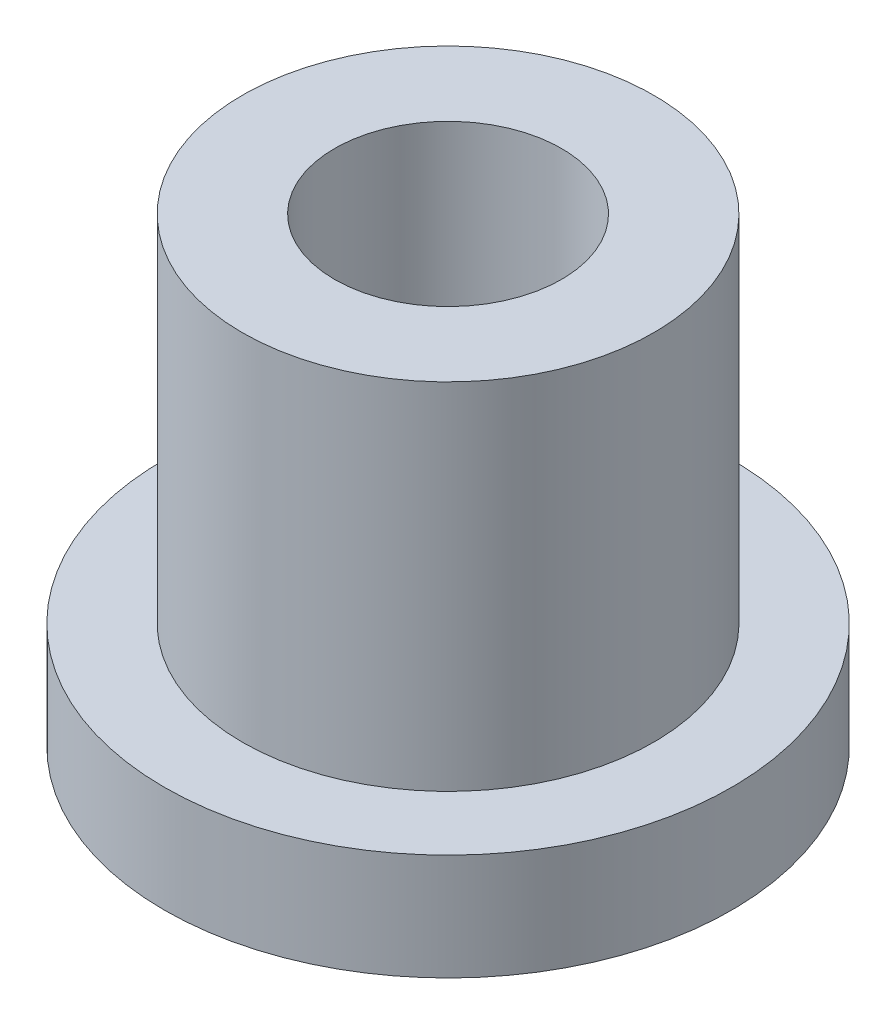
SolidWorks part; units mm, degrees
ref_plane "前视基准面" through (0, 0, 0) normal (0, 0, 1) x (1, 0, 0)
ref_plane "上视基准面" through (0, 0, 0) normal (0, 1, 0) x (1, 0, 0)
ref_plane "右视基准面" through (0, 0, 0) normal (1, 0, 0) x (0, 0, -1)
sketch "草图1" plane through (0, 0, 0) normal (0, 1, 0) x (1, 0, 0)
  circle A0 centre (0, 0) radius 4
  dimension "D1" = 8
extrude "凸台-拉伸1" add sketch "草图1" along normal blind 1.5
sketch "草图2" plane through (0, 1.5, 0) normal (0, 1, 0) x (1, 0, 0)
  circle A0 centre (0, 0) radius 2.9
  dimension "D1" = 5.8
extrude "凸台-拉伸2" add sketch "草图2" along normal blind 5
sketch "草图3" plane through (0, 6.5, 0) normal (0, 1, 0) x (1, 0, 0)
  circle A0 centre (0, 0) radius 1.6
  dimension "D1" = 3.2
extrude "切除-拉伸1" cut sketch "草图3" against normal up to next
